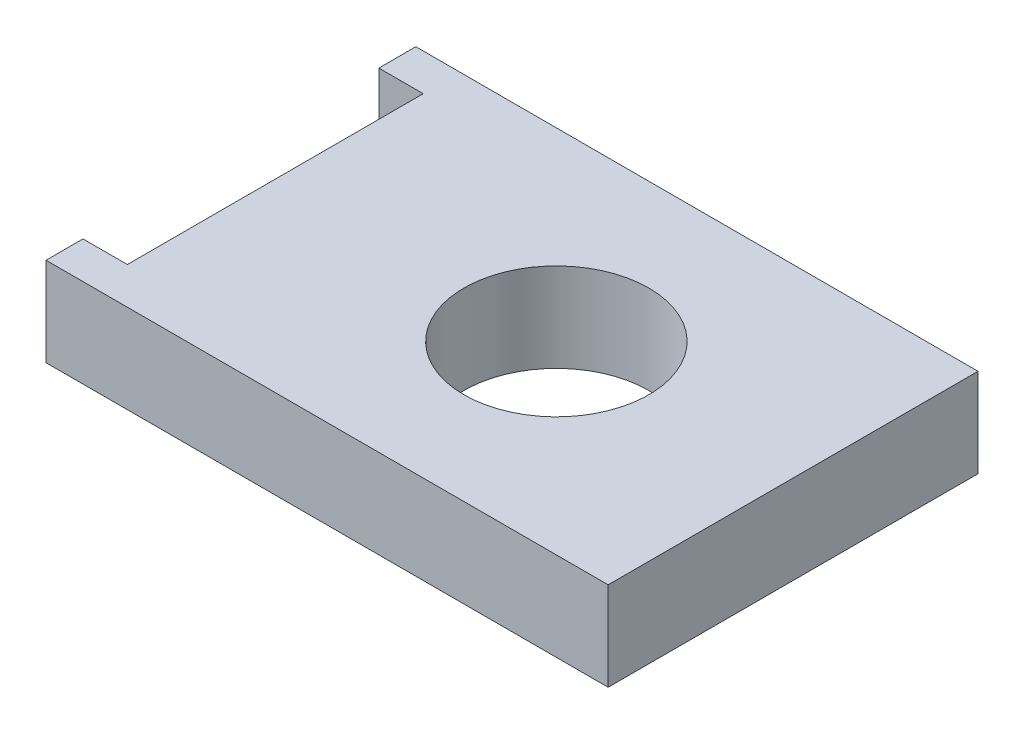
SolidWorks part; units mm, degrees
ref_plane "Front Plane" through (0, 0, 0) normal (0, 0, 1) x (1, 0, 0)
ref_plane "Top Plane" through (0, 0, 0) normal (0, 1, 0) x (1, 0, 0)
ref_plane "Right Plane" through (0, 0, 0) normal (1, 0, 0) x (0, 0, -1)
sketch "Sketch1" plane through (0, 0, 0) normal (0, 1, 0) x (1, 0, 0)
  line L0 (-19, 10) -> (-16, 10)
  line L1 (19, -12.5) -> (-19, -12.5)
  line L2 (19, -12.5) -> (19, 12.5)
  line L3 (19, 12.5) -> (-19, 12.5)
  line L4 (-19, -12.5) -> (-19, -10)
  line L5 (19, -12.5) -> (-19, 12.5) construction
  line L6 (19, 12.5) -> (-19, -12.5) construction
  line L7 (-16, 10) -> (-16, -10)
  line L8 (-16, -10) -> (-19, -10)
  line L9 (0, 0) -> (20.8273, 0) construction
  line L10 (-19, 10) -> (-19, 12.5)
  circle A0 centre (3, 0) radius 6.25
  point P0 (0, 0)
  dimension "D5" = 12.5
  dimension "D6" = 16
  dimension "D1" = 20
  dimension "D2" = 3
  dimension "D3" = 38
  dimension "D4" = 25
extrude "Boss-Extrude1" add sketch "Sketch1" along normal mid plane 6
